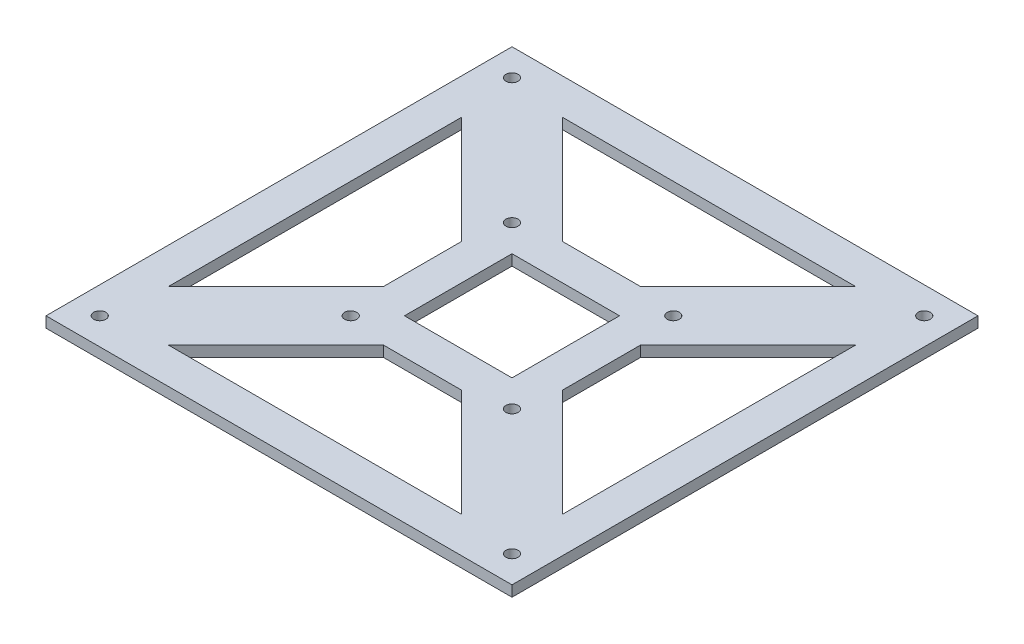
SolidWorks part; units mm, degrees
ref_plane "Front Plane" through (0, 0, 0) normal (0, 0, 1) x (1, 0, 0)
ref_plane "Top Plane" through (0, 0, 0) normal (0, 1, 0) x (1, 0, 0)
ref_plane "Right Plane" through (0, 0, 0) normal (1, 0, 0) x (0, 0, -1)
sketch "Sketch1" plane through (0, 0, 0) normal (0, 1, 0) x (1, 0, 0)
  line L0 (-55, 55) -> (-55, -55)
  line L1 (-65, 65) -> (65, 65)
  line L2 (-65, 65) -> (-65, -65)
  line L3 (-65, -65) -> (65, -65)
  line L4 (65, 65) -> (65, -65)
  line L5 (-65, 65) -> (65, -65) construction
  line L6 (-65, -65) -> (65, 65) construction
  line L7 (-55, -55) -> (55, -55)
  line L8 (55, 55) -> (55, -55)
  line L9 (-55, 55) -> (55, 55)
  line L10 (-15, 15) -> (-15, -15)
  line L11 (-15, -15) -> (15, -15)
  line L12 (15, 15) -> (15, -15)
  line L13 (-15, 15) -> (15, 15)
  line L14 (-25, 25) -> (-25, -25)
  line L15 (-25, -25) -> (25, -25)
  line L16 (25, 25) -> (25, -25)
  line L17 (-25, 25) -> (25, 25)
  line L18 (-55, -55) -> (-25, -25)
  line L19 (-47.9289, -62.0711) -> (-10.8579, -25)
  line L20 (-62.0711, -47.9289) -> (-25, -10.8579)
  line L21 (-62.0711, -47.9289) -> (-32.0711, -17.9289) construction
  line L22 (-47.9289, -62.0711) -> (-17.9289, -32.0711) construction
  line L23 (-47.9289, 62.0711) -> (-10.8579, 25)
  line L24 (-62.0711, 47.9289) -> (-25, 10.8579)
  line L25 (62.0711, 47.9289) -> (25, 10.8579)
  line L26 (47.9289, 62.0711) -> (10.8579, 25)
  line L27 (47.9289, -62.0711) -> (10.8579, -25)
  line L28 (62.0711, -47.9289) -> (25, -10.8579)
  point P0 (0, 0)
  point P39 (0, 0)
  dimension "D1" = 130
  dimension "D2" = 10
  dimension "D3" = 40
  dimension "D4" = 10
  dimension "D5" = 10
  dimension "D6" = 10
  dimension "D7" = 4
extrude "Boss-Extrude1" add sketch "Sketch1" along normal blind 3
sketch "Sketch2" plane through (0, 3, 0) normal (0, 1, 0) x (1, 0, 0)
  line L1 (-57.5, -57.5) -> (57.5, -57.5)
  line L2 (-57.5, -57.5) -> (-57.5, 57.5)
  line L3 (-57.5, 57.5) -> (57.5, 57.5)
  line L4 (57.5, -57.5) -> (57.5, 57.5)
  line L5 (-57.5, -57.5) -> (57.5, 57.5) construction
  line L6 (-57.5, 57.5) -> (57.5, -57.5) construction
  circle A0 centre (-57.5, 57.5) radius 1.7
  circle A1 centre (57.5, 57.5) radius 1.7
  circle A2 centre (57.5, -57.5) radius 1.7
  circle A3 centre (-57.5, -57.5) radius 1.7
  point P0 (0, 0)
  dimension "D2" = 3.4
  dimension "D1" = 115
extrude "Cut-Extrude1" cut sketch "Sketch2" against normal blind 3 contours L3 A0 L2 | L2 A0 L3 | L2 A3 L1 | L1 A3 L2 | L1 A2 L4 | L4 A2 L1 | L4 A1 L3 | L3 A1 L4
sketch "Sketch3" plane through (0, 3, 0) normal (0, 1, 0) x (1, 0, 0)
  line L1 (-22.5, -22.5) -> (22.5, -22.5)
  line L2 (-22.5, -22.5) -> (-22.5, 22.5)
  line L3 (-22.5, 22.5) -> (22.5, 22.5)
  line L4 (22.5, -22.5) -> (22.5, 22.5)
  line L5 (-22.5, -22.5) -> (22.5, 22.5) construction
  line L6 (-22.5, 22.5) -> (22.5, -22.5) construction
  circle A0 centre (-22.5, 22.5) radius 1.7
  circle A1 centre (22.5, 22.5) radius 1.7
  circle A2 centre (22.5, -22.5) radius 1.7
  circle A3 centre (-22.5, -22.5) radius 1.7
  point P0 (0, 0)
  dimension "D2" = 3.4
  dimension "D1" = 45
extrude "Cut-Extrude2" cut sketch "Sketch3" against normal blind 3 contours L2 A3 L1 | L1 A3 L2 | L2 A0 L3 | L3 A0 L2 | L1 A2 L4 | L4 A2 L1 | L4 A1 L3 | L3 A1 L4
